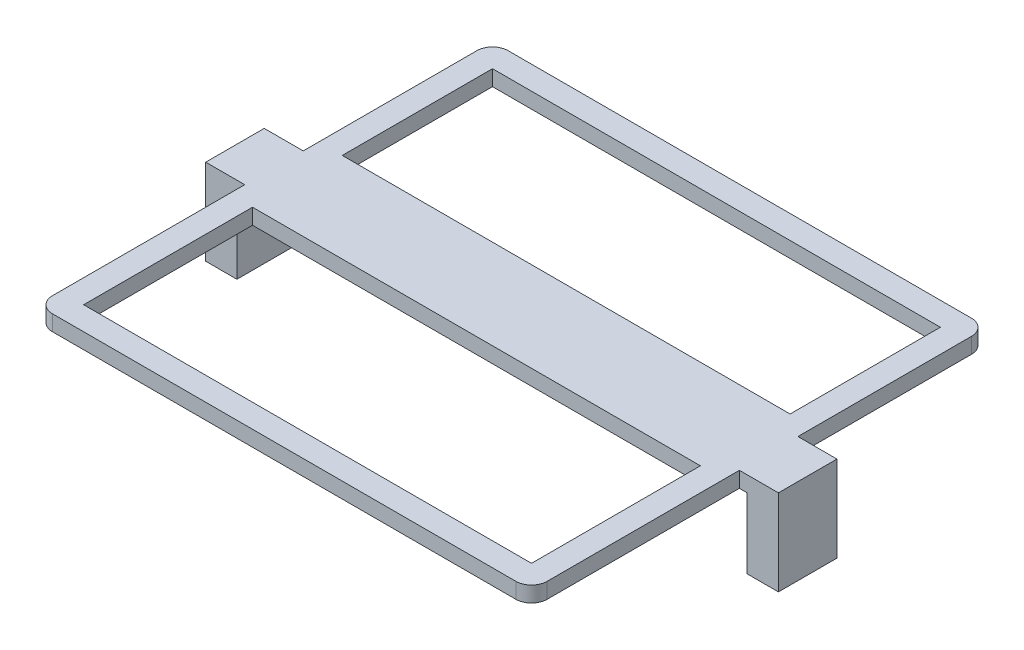
SolidWorks part; units mm, degrees
ref_plane "Спереди" through (0, 0, 0) normal (0, 0, 1) x (1, 0, 0)
ref_plane "Сверху" through (0, 0, 0) normal (0, 1, 0) x (1, 0, 0)
ref_plane "Справа" through (0, 0, 0) normal (1, 0, 0) x (0, 0, -1)
other "Configuration Table"
sketch "Эскиз1" plane through (0, 0, 0) normal (0, 1, 0) x (1, 0, 0)
  line L0 (63.4, -24.255) -> (68.4, -24.255)
  line L1 (0, 0) -> (63.4, 0)
  line L2 (0, 0) -> (0, -24.255)
  line L3 (0, -58.4) -> (63.4, -58.4)
  line L4 (63.4, 0) -> (63.4, -24.255)
  line L5 (-5, -24.255) -> (0, -24.255)
  line L6 (-5, -24.255) -> (-5, -31.755)
  line L7 (-5, -31.755) -> (0, -31.755)
  line L8 (68.4, -24.255) -> (68.4, -31.755)
  line L9 (63.4, -31.755) -> (68.4, -31.755)
  line L10 (0, -31.755) -> (0, -58.4)
  line L11 (63.4, -31.755) -> (63.4, -58.4)
  line L13 (3, -3) -> (60.4, -3)
  line L14 (3, -3) -> (3, -22.255)
  line L15 (3, -22.255) -> (60.4, -22.255)
  line L16 (60.4, -3) -> (60.4, -22.255)
  line L17 (3, -33.755) -> (60.4, -33.755)
  line L18 (3, -33.755) -> (3, -55.4)
  line L19 (3, -55.4) -> (60.4, -55.4)
  line L20 (60.4, -33.755) -> (60.4, -55.4)
  dimension "D1" = 63.4
  dimension "D2" = 58.4
  dimension "D3" = 7.5
  dimension "D4" = 24.255
  dimension "D5" = 5
  dimension "D6" = 5
  dimension "D7" = 3
  dimension "D8" = 3
  dimension "D9" = 3
  dimension "D10" = 3
  dimension "D11" = 2
  dimension "D12" = 2
  dimension "D13" = 3
  dimension "D14" = 3
extrude "Бобышка-Вытянуть1" add sketch "Эскиз1" along normal blind 2
fillet "Скругление1" radius 2 4 edges at (0, 1, 0) (63.4, 1, 0) (0, 1, 58.4) (63.4, 1, 58.4)
sketch "Эскиз2" plane through (0, 0, 0) normal (0, -1, 0) x (-1, 0, 0)
  line L0 (0, -24.255) -> (5, -24.255) construction
  line L1 (5, -31.755) -> (1, -31.755)
  line L2 (5, -31.755) -> (5, -24.255)
  line L3 (5, -24.255) -> (1, -24.255)
  line L4 (1, -31.755) -> (1, -24.255)
  line L6 (-68.4, -31.755) -> (-64.4, -31.755)
  line L7 (-68.4, -31.755) -> (-68.4, -24.255)
  line L8 (-68.4, -24.255) -> (-64.4, -24.255)
  line L9 (-64.4, -31.755) -> (-64.4, -24.255)
  point P14 (0, 0)
  point P15 (0, 0)
  dimension "D1" = 4
  dimension "D2" = 4
extrude "Бобышка-Вытянуть2" add sketch "Эскиз2" along normal blind 9
